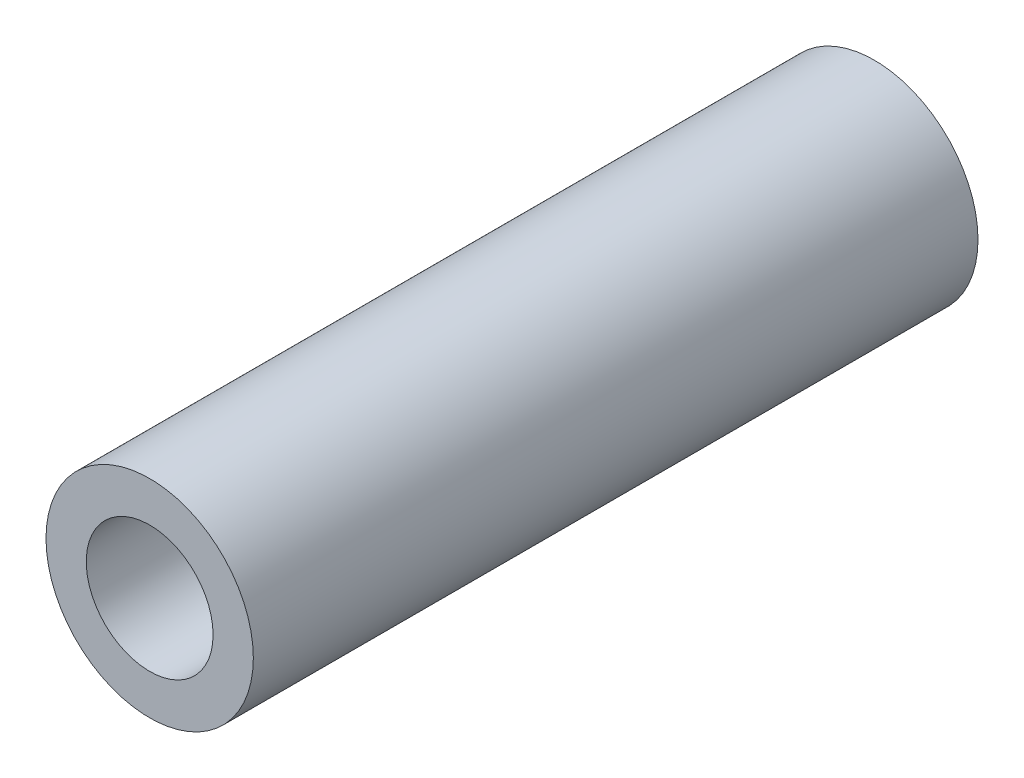
SolidWorks part; units mm, degrees
material "ABS"
ref_plane "Front Plane" through (0, 0, 0) normal (0, 0, 1) x (1, 0, 0)
ref_plane "Top Plane" through (0, 0, 0) normal (0, 1, 0) x (1, 0, 0)
ref_plane "Right Plane" through (0, 0, 0) normal (1, 0, 0) x (0, 0, -1)
sketch "Sketch1" plane through (0, 0, 0) normal (0, 0, 1) x (1, 0, 0)
  circle A0 centre (33, 0) radius 2.575
  dimension "D1" = 5.15
extrude "Boss-Extrude1" add sketch "Sketch1" along normal blind 18
sketch "Sketch3" plane through (0, 0, 18) normal (0, 0, 1) x (1, 0, 0)
  circle A0 centre (33, 0) radius 1.575
  circle A1 centre (33, 0) radius 2.1
  dimension "D1" = 3.15
  dimension "D2" = 4.2
extrude "Cut-Extrude1" cut sketch "Sketch3" against normal up to next contours A0
equation "\"RingPostIn\"=5.15"
equation "\"D1@Sketch1\"=\"RingPostIn\""
equation "\"RingPinShaft\"= 5.05"
equation "\"CenterBearingOut\"=32.05"
equation "\"m3Thru\"=3.15"
equation "\"D1@Sketch3\"=\"m3Thru\""
equation "\"m3Insert\"=4.2"
equation "\"D2@Sketch3\"=\"m3Insert\""
